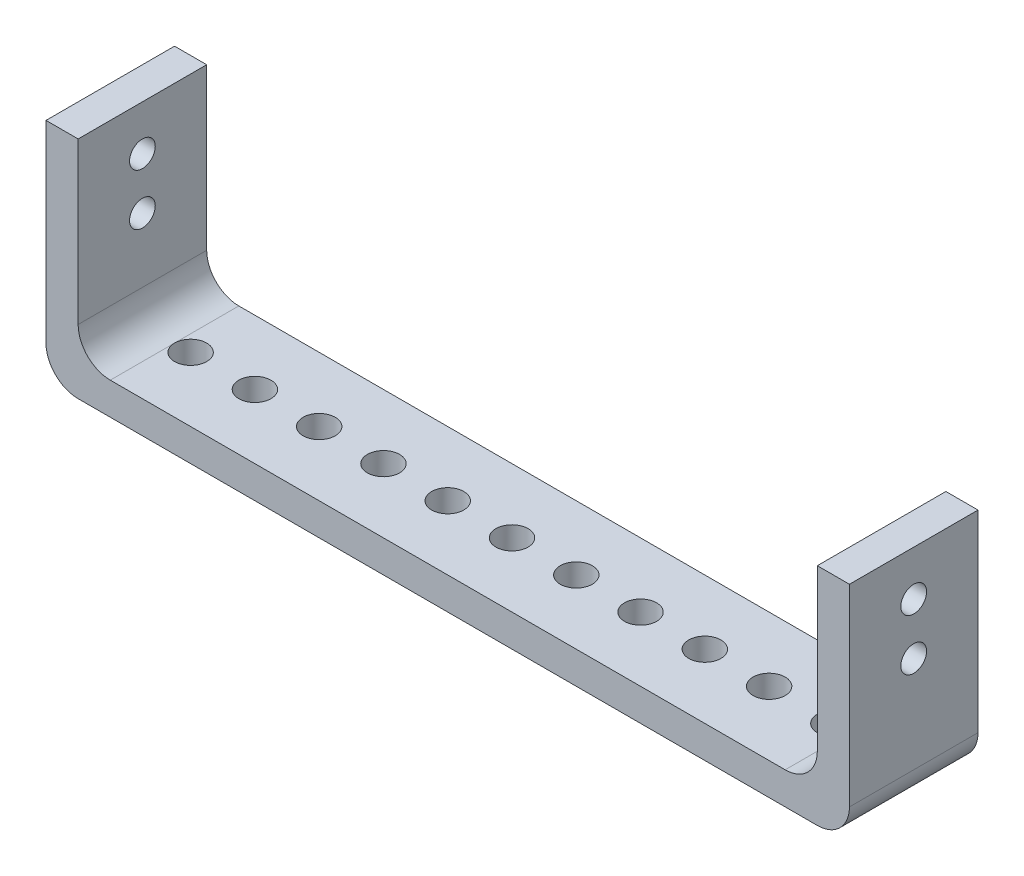
SolidWorks part; units mm, degrees
material "6061 Alloy"
ref_plane "Front Plane" through (0, 0, 0) normal (0, 0, 1) x (1, 0, 0)
ref_plane "Top Plane" through (0, 0, 0) normal (0, 1, 0) x (1, 0, 0)
ref_plane "Right Plane" through (0, 0, 0) normal (1, 0, 0) x (0, 0, -1)
sketch "Sketch1" plane through (0, 0, 0) normal (0, 0, 1) x (1, 0, 0)
  line L0 (-57.5, 0) -> (57.5, 0)
  line L1 (62.5, 5) -> (62.5, 35)
  line L2 (62.5, 35) -> (57.5, 35)
  line L3 (57.5, 35) -> (57.5, 10)
  line L4 (52.5, 5) -> (-52.5, 5)
  line L5 (-57.5, 10) -> (-57.5, 35)
  line L6 (-57.5, 35) -> (-62.5, 35)
  line L7 (-62.5, 35) -> (-62.5, 5)
  arc A0 (-57.5, 0) -> (-62.5, 5) centre (-57.5, 5) cw
  arc A1 (-52.5, 5) -> (-57.5, 10) centre (-52.5, 10) cw
  arc A2 (57.5, 10) -> (52.5, 5) centre (52.5, 10) cw
  arc A3 (57.5, 0) -> (62.5, 5) centre (57.5, 5) ccw
  point P11 (-62.5, 0)
  point P18 (62.5, 0)
  dimension "D6" = 5
  dimension "D7" = 5
  dimension "D8" = 5
  dimension "D9" = 5
  dimension "D1" = 125
  dimension "D2" = 5
  dimension "D3" = 5
  dimension "D5" = 35
extrude "Boss-Extrude1" add sketch "Sketch1" along normal mid plane 20
sketch "Sketch2" plane through (62.5, 0, 0) normal (1, 0, 0) x (0, 0, -1)
  circle A0 centre (0, 20) radius 2
  dimension "D2" = 4
  dimension "D1" = 20
extrude "Cut-Extrude1" cut sketch "Sketch2" against normal through all both and the other way through all
pattern_linear "LPattern2" count 2 spacing 8 along (0, 1, 0) of "Cut-Extrude1"
sketch "Sketch3" plane through (0, 0, 0) normal (0, -1, 0) x (1, 0, 0)
  line L0 (0, 0) -> (-10, 0) construction
  line L1 (0, 0) -> (10, 0) construction
  circle A0 centre (0, 0) radius 2.5
  circle A1 centre (-10, 0) radius 2.5
  circle A2 centre (-20, 0) radius 2.5
  circle A3 centre (-30, 0) radius 2.5
  circle A4 centre (-40, 0) radius 2.5
  circle A5 centre (-50, 0) radius 2.5
  circle A6 centre (10, 0) radius 2.5
  circle A7 centre (20, 0) radius 2.5
  circle A8 centre (30, 0) radius 2.5
  circle A9 centre (40, 0) radius 2.5
  circle A10 centre (50, 0) radius 2.5
  dimension "D1" = 5
  dimension "D3" = 10
  dimension "D5" = 10
  dimension "D2" = 6
  dimension "D4" = 6
extrude "Cut-Extrude2" cut sketch "Sketch3" against normal through all both and the other way through all
